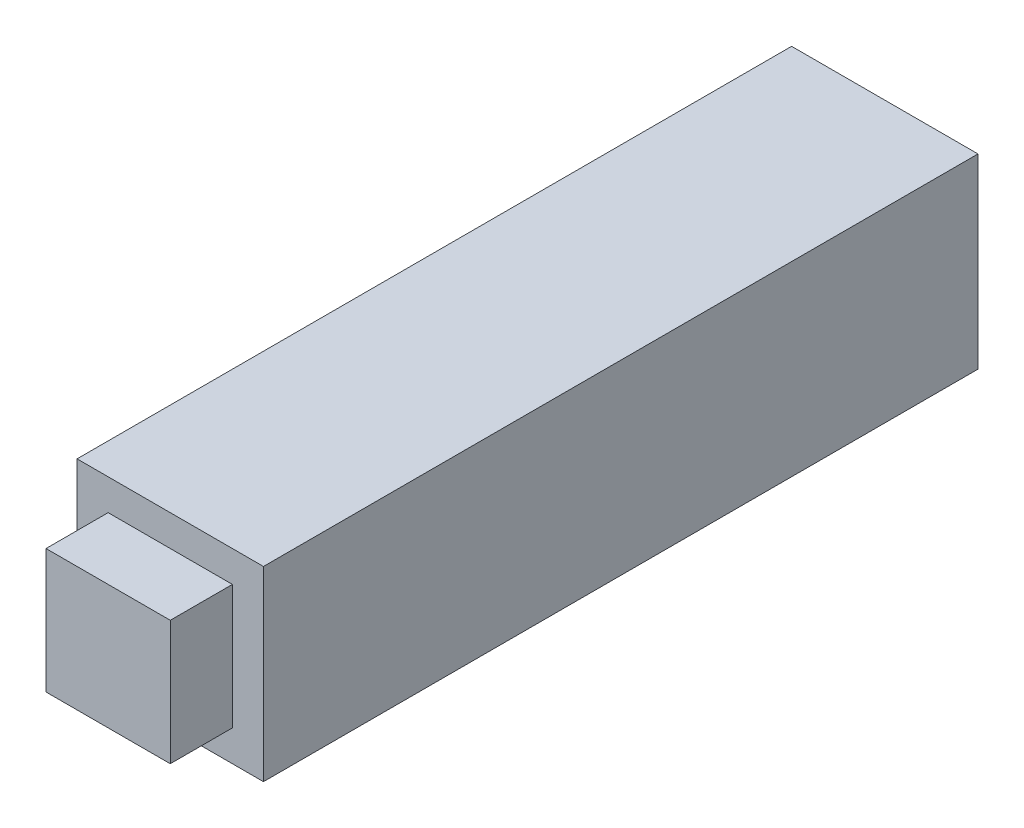
SolidWorks part; units mm, degrees
ref_plane "Front Plane" through (0, 0, 0) normal (0, 0, 1) x (1, 0, 0)
ref_plane "Top Plane" through (0, 0, 0) normal (0, 1, 0) x (1, 0, 0)
ref_plane "Right Plane" through (0, 0, 0) normal (1, 0, 0) x (0, 0, -1)
sketch "Sketch1" plane through (0, 0, 0) normal (0, 0, 1) x (1, 0, 0)
  line L1 (-15, 15) -> (15, 15)
  line L2 (-15, 15) -> (-15, -15)
  line L3 (-15, -15) -> (15, -15)
  line L4 (15, 15) -> (15, -15)
  line L5 (-15, 15) -> (15, -15) construction
  line L6 (-15, -15) -> (15, 15) construction
  point P0 (0, 0)
  dimension "D1" = 30
  dimension "D2" = 30
extrude "Boss-Extrude1" add sketch "Sketch1" along normal blind 115
sketch "Sketch2" plane through (0, 0, 115) normal (0, 0, 1) x (1, 0, 0)
  line L0 (15, 15) -> (-15, 15) construction
  line L1 (-10, 10) -> (10, 10)
  line L2 (-10, 10) -> (-10, -10)
  line L3 (-10, -10) -> (10, -10)
  line L4 (10, 10) -> (10, -10)
  line L5 (-10, 10) -> (10, -10) construction
  line L6 (-10, -10) -> (10, 10) construction
  line L7 (-15, 15) -> (-15, -15) construction
  point P0 (0, 0)
  dimension "D1" = 5
  dimension "D2" = 5
extrude "Boss-Extrude2" add sketch "Sketch2" along normal blind 10
